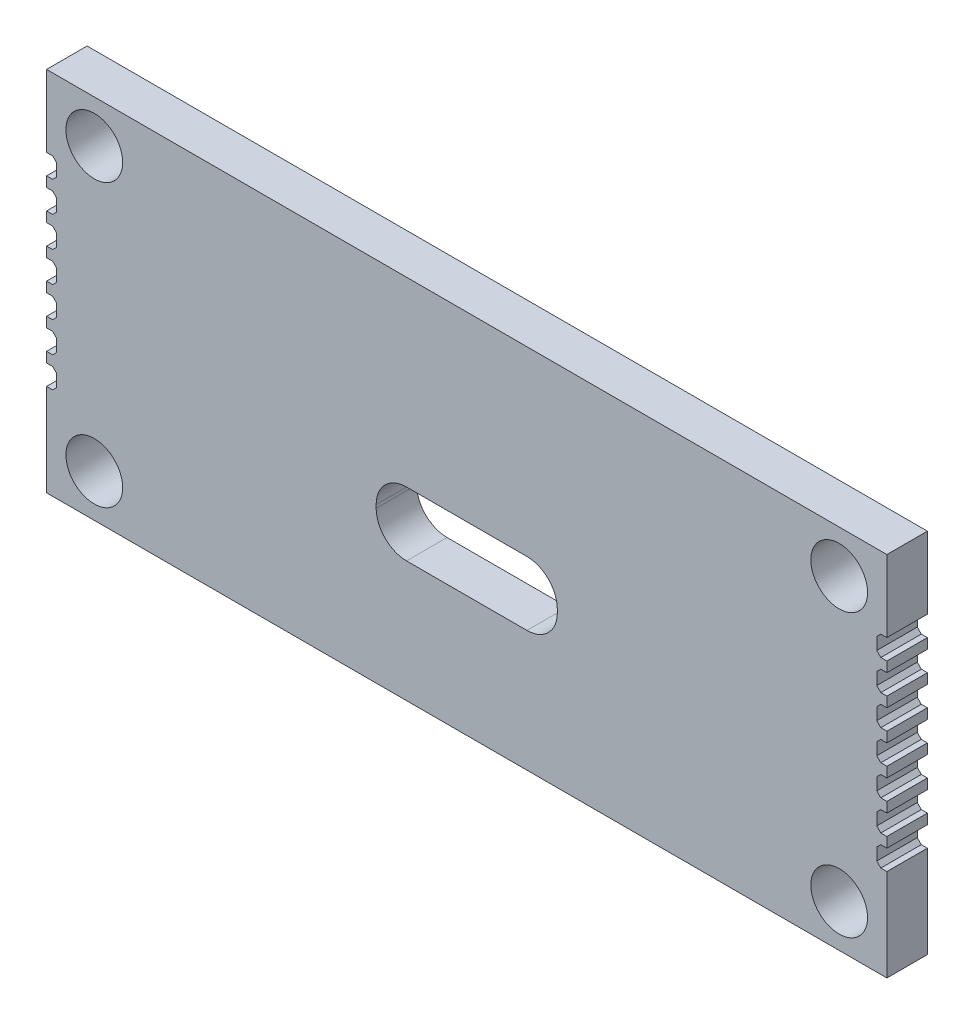
SolidWorks part; units mm, degrees
ref_plane "前视基准面" through (0, 0, 0) normal (0, 0, 1) x (1, 0, 0)
ref_plane "上视基准面" through (0, 0, 0) normal (0, 1, 0) x (1, 0, 0)
ref_plane "右视基准面" through (0, 0, 0) normal (1, 0, 0) x (0, 0, -1)
sketch "草图1" plane through (0, 0, 0) normal (0, 0, 1) x (1, 0, 0)
  line L4 (20.7373, 10.05) -> (20.7373, 13.6)
  line L5 (-20.7373, -4.5) -> (20.7373, -4.5)
  line L6 (-20.7373, 0.05) -> (-20.7373, -4.5)
  line L7 (20.7373, 13.6) -> (-20.7373, 13.6)
  line L8 (20.7373, 10.05) -> (20.7373, 13.6)
  line L9 (-20.7373, -4.5) -> (20.7373, -4.5)
  line L10 (-20.7373, 0.05) -> (-20.7373, -4.5)
  line L11 (20.7373, 13.6) -> (-20.7373, 13.6)
  line L184 (20.4373, 1.55) -> (20.2373, 1.75)
  line L185 (20.4373, 1.55) -> (20.2373, 1.75)
  line L186 (20.7373, 1.55) -> (20.4373, 1.55)
  line L187 (20.7373, 1.55) -> (20.4373, 1.55)
  line L188 (20.7373, 1.05) -> (20.7373, 1.55)
  line L189 (20.7373, 1.05) -> (20.7373, 1.55)
  line L190 (20.4373, 1.05) -> (20.7373, 1.05)
  line L191 (20.4373, 1.05) -> (20.7373, 1.05)
  line L192 (20.2373, 0.85) -> (20.4373, 1.05)
  line L193 (20.2373, 0.85) -> (20.4373, 1.05)
  line L194 (20.2373, 0.25) -> (20.2373, 0.85)
  line L195 (20.2373, 0.25) -> (20.2373, 0.85)
  line L196 (20.4373, 0.05) -> (20.2373, 0.25)
  line L197 (20.4373, 0.05) -> (20.2373, 0.25)
  line L198 (20.7373, 0.05) -> (20.4373, 0.05)
  line L199 (20.7373, 0.05) -> (20.4373, 0.05)
  line L200 (20.7373, -4.5) -> (20.7373, 0.05)
  line L201 (20.7373, -4.5) -> (20.7373, 0.05)
  line L202 (-20.4373, 0.05) -> (-20.7373, 0.05)
  line L203 (-20.4373, 0.05) -> (-20.7373, 0.05)
  line L204 (-20.2373, 0.25) -> (-20.4373, 0.05)
  line L205 (-20.2373, 0.25) -> (-20.4373, 0.05)
  line L206 (-20.2373, 0.85) -> (-20.2373, 0.25)
  line L207 (-20.2373, 0.85) -> (-20.2373, 0.25)
  line L208 (-20.4373, 1.05) -> (-20.2373, 0.85)
  line L209 (-20.4373, 1.05) -> (-20.2373, 0.85)
  line L210 (-20.7373, 1.05) -> (-20.4373, 1.05)
  line L211 (-20.7373, 1.05) -> (-20.4373, 1.05)
  line L212 (-20.7373, 1.55) -> (-20.7373, 1.05)
  line L213 (-20.7373, 1.55) -> (-20.7373, 1.05)
  line L214 (-20.4373, 1.55) -> (-20.7373, 1.55)
  line L215 (-20.4373, 1.55) -> (-20.7373, 1.55)
  line L216 (-20.2373, 1.75) -> (-20.4373, 1.55)
  line L217 (-20.2373, 1.75) -> (-20.4373, 1.55)
  line L218 (-20.2373, 2.35) -> (-20.2373, 1.75)
  line L219 (-20.2373, 2.35) -> (-20.2373, 1.75)
  line L220 (-20.4373, 2.55) -> (-20.2373, 2.35)
  line L221 (-20.4373, 2.55) -> (-20.2373, 2.35)
  line L222 (-20.7373, 2.55) -> (-20.4373, 2.55)
  line L223 (-20.7373, 2.55) -> (-20.4373, 2.55)
  line L224 (-20.7373, 3.05) -> (-20.7373, 2.55)
  line L225 (-20.7373, 3.05) -> (-20.7373, 2.55)
  line L226 (-20.4373, 3.05) -> (-20.7373, 3.05)
  line L227 (-20.4373, 3.05) -> (-20.7373, 3.05)
  line L228 (-20.2373, 3.25) -> (-20.4373, 3.05)
  line L229 (-20.2373, 3.25) -> (-20.4373, 3.05)
  line L230 (-20.2373, 3.85) -> (-20.2373, 3.25)
  line L231 (-20.2373, 3.85) -> (-20.2373, 3.25)
  line L232 (-20.4373, 4.05) -> (-20.2373, 3.85)
  line L233 (-20.4373, 4.05) -> (-20.2373, 3.85)
  line L234 (-20.7373, 4.05) -> (-20.4373, 4.05)
  line L235 (-20.7373, 4.05) -> (-20.4373, 4.05)
  line L236 (-20.7373, 4.55) -> (-20.7373, 4.05)
  line L237 (-20.7373, 4.55) -> (-20.7373, 4.05)
  line L238 (-20.4373, 4.55) -> (-20.7373, 4.55)
  line L239 (-20.4373, 4.55) -> (-20.7373, 4.55)
  line L240 (-20.2373, 4.75) -> (-20.4373, 4.55)
  line L241 (-20.2373, 4.75) -> (-20.4373, 4.55)
  line L242 (-20.2373, 5.35) -> (-20.2373, 4.75)
  line L243 (-20.2373, 5.35) -> (-20.2373, 4.75)
  line L244 (-20.4373, 5.55) -> (-20.2373, 5.35)
  line L245 (-20.4373, 5.55) -> (-20.2373, 5.35)
  line L246 (-20.7373, 5.55) -> (-20.4373, 5.55)
  line L247 (-20.7373, 5.55) -> (-20.4373, 5.55)
  line L248 (-20.7373, 6.05) -> (-20.7373, 5.55)
  line L249 (-20.7373, 6.05) -> (-20.7373, 5.55)
  line L250 (-20.4373, 6.05) -> (-20.7373, 6.05)
  line L251 (-20.4373, 6.05) -> (-20.7373, 6.05)
  line L252 (-20.2373, 6.25) -> (-20.4373, 6.05)
  line L253 (-20.2373, 6.25) -> (-20.4373, 6.05)
  line L254 (-20.2373, 6.85) -> (-20.2373, 6.25)
  line L255 (-20.2373, 6.85) -> (-20.2373, 6.25)
  line L256 (-20.4373, 7.05) -> (-20.2373, 6.85)
  line L257 (-20.4373, 7.05) -> (-20.2373, 6.85)
  line L258 (-20.7373, 7.05) -> (-20.4373, 7.05)
  line L259 (-20.7373, 7.05) -> (-20.4373, 7.05)
  line L260 (-20.7373, 7.55) -> (-20.7373, 7.05)
  line L261 (-20.7373, 7.55) -> (-20.7373, 7.05)
  line L262 (-20.4373, 7.55) -> (-20.7373, 7.55)
  line L263 (-20.4373, 7.55) -> (-20.7373, 7.55)
  line L264 (-20.2373, 7.75) -> (-20.4373, 7.55)
  line L265 (-20.2373, 7.75) -> (-20.4373, 7.55)
  line L266 (-20.2373, 8.35) -> (-20.2373, 7.75)
  line L267 (-20.2373, 8.35) -> (-20.2373, 7.75)
  line L268 (-20.4373, 8.55) -> (-20.2373, 8.35)
  line L269 (-20.4373, 8.55) -> (-20.2373, 8.35)
  line L270 (-20.7373, 8.55) -> (-20.4373, 8.55)
  line L271 (-20.7373, 8.55) -> (-20.4373, 8.55)
  line L272 (-20.7373, 9.05) -> (-20.7373, 8.55)
  line L273 (-20.7373, 9.05) -> (-20.7373, 8.55)
  line L274 (-20.4373, 9.05) -> (-20.7373, 9.05)
  line L275 (-20.4373, 9.05) -> (-20.7373, 9.05)
  line L276 (-20.2373, 9.25) -> (-20.4373, 9.05)
  line L277 (-20.2373, 9.25) -> (-20.4373, 9.05)
  line L278 (-20.2373, 9.85) -> (-20.2373, 9.25)
  line L279 (-20.2373, 9.85) -> (-20.2373, 9.25)
  line L280 (-20.4373, 10.05) -> (-20.2373, 9.85)
  line L281 (-20.4373, 10.05) -> (-20.2373, 9.85)
  line L282 (-20.7373, 10.05) -> (-20.4373, 10.05)
  line L283 (-20.7373, 10.05) -> (-20.4373, 10.05)
  line L284 (-20.7373, 13.6) -> (-20.7373, 10.05)
  line L285 (-20.7373, 13.6) -> (-20.7373, 10.05)
  line L286 (20.4373, 10.05) -> (20.7373, 10.05)
  line L287 (20.4373, 10.05) -> (20.7373, 10.05)
  line L288 (20.2373, 9.85) -> (20.4373, 10.05)
  line L289 (20.2373, 9.85) -> (20.4373, 10.05)
  line L290 (20.2373, 9.25) -> (20.2373, 9.85)
  line L291 (20.2373, 9.25) -> (20.2373, 9.85)
  line L292 (20.4373, 9.05) -> (20.2373, 9.25)
  line L293 (20.4373, 9.05) -> (20.2373, 9.25)
  line L294 (20.7373, 9.05) -> (20.4373, 9.05)
  line L295 (20.7373, 9.05) -> (20.4373, 9.05)
  line L296 (20.7373, 8.55) -> (20.7373, 9.05)
  line L297 (20.7373, 8.55) -> (20.7373, 9.05)
  line L298 (20.4373, 8.55) -> (20.7373, 8.55)
  line L299 (20.4373, 8.55) -> (20.7373, 8.55)
  line L300 (20.2373, 8.35) -> (20.4373, 8.55)
  line L301 (20.2373, 8.35) -> (20.4373, 8.55)
  line L302 (20.2373, 7.75) -> (20.2373, 8.35)
  line L303 (20.2373, 7.75) -> (20.2373, 8.35)
  line L304 (20.4373, 7.55) -> (20.2373, 7.75)
  line L305 (20.4373, 7.55) -> (20.2373, 7.75)
  line L306 (20.7373, 7.55) -> (20.4373, 7.55)
  line L307 (20.7373, 7.55) -> (20.4373, 7.55)
  line L308 (20.7373, 7.05) -> (20.7373, 7.55)
  line L309 (20.7373, 7.05) -> (20.7373, 7.55)
  line L310 (20.4373, 7.05) -> (20.7373, 7.05)
  line L311 (20.4373, 7.05) -> (20.7373, 7.05)
  line L312 (20.2373, 6.85) -> (20.4373, 7.05)
  line L313 (20.2373, 6.85) -> (20.4373, 7.05)
  line L314 (20.2373, 6.25) -> (20.2373, 6.85)
  line L315 (20.2373, 6.25) -> (20.2373, 6.85)
  line L316 (20.4373, 6.05) -> (20.2373, 6.25)
  line L317 (20.4373, 6.05) -> (20.2373, 6.25)
  line L318 (20.7373, 6.05) -> (20.4373, 6.05)
  line L319 (20.7373, 6.05) -> (20.4373, 6.05)
  line L320 (20.7373, 5.55) -> (20.7373, 6.05)
  line L321 (20.7373, 5.55) -> (20.7373, 6.05)
  line L322 (20.4373, 5.55) -> (20.7373, 5.55)
  line L323 (20.4373, 5.55) -> (20.7373, 5.55)
  line L324 (20.2373, 5.35) -> (20.4373, 5.55)
  line L325 (20.2373, 5.35) -> (20.4373, 5.55)
  line L326 (20.2373, 4.75) -> (20.2373, 5.35)
  line L327 (20.2373, 4.75) -> (20.2373, 5.35)
  line L328 (20.4373, 4.55) -> (20.2373, 4.75)
  line L329 (20.4373, 4.55) -> (20.2373, 4.75)
  line L330 (20.7373, 4.55) -> (20.4373, 4.55)
  line L331 (20.7373, 4.55) -> (20.4373, 4.55)
  line L332 (20.7373, 4.05) -> (20.7373, 4.55)
  line L333 (20.7373, 4.05) -> (20.7373, 4.55)
  line L334 (20.4373, 4.05) -> (20.7373, 4.05)
  line L335 (20.4373, 4.05) -> (20.7373, 4.05)
  line L336 (20.2373, 3.85) -> (20.4373, 4.05)
  line L337 (20.2373, 3.85) -> (20.4373, 4.05)
  line L338 (20.2373, 3.25) -> (20.2373, 3.85)
  line L339 (20.2373, 3.25) -> (20.2373, 3.85)
  line L340 (20.4373, 3.05) -> (20.2373, 3.25)
  line L341 (20.4373, 3.05) -> (20.2373, 3.25)
  line L342 (20.7373, 3.05) -> (20.4373, 3.05)
  line L343 (20.7373, 3.05) -> (20.4373, 3.05)
  line L344 (20.7373, 2.55) -> (20.7373, 3.05)
  line L345 (20.7373, 2.55) -> (20.7373, 3.05)
  line L346 (20.4373, 2.55) -> (20.7373, 2.55)
  line L347 (20.4373, 2.55) -> (20.7373, 2.55)
  line L348 (20.2373, 2.35) -> (20.4373, 2.55)
  line L349 (20.2373, 2.35) -> (20.4373, 2.55)
  line L350 (20.2373, 1.75) -> (20.2373, 2.35)
  line L351 (20.2373, 1.75) -> (20.2373, 2.35)
  circle A0 centre (-18.3831, 11.5) radius 1.4 construction
  circle A1 centre (-18.3831, -2.4) radius 1.4 construction
  circle A2 centre (18.3831, -2.4) radius 1.4 construction
  circle A3 centre (18.3831, 11.5) radius 1.4 construction
  circle A4 centre (-18.3831, 11.5) radius 1.4
  circle A5 centre (-18.3831, -2.4) radius 1.4
  circle A6 centre (18.3831, -2.4) radius 1.4
  circle A7 centre (18.3831, 11.5) radius 1.4
  dimension "D1" = 0
extrude "凸台-拉伸2" add sketch "草图1" along normal blind 2 contours A4 | A5 | A7 | A6 | L8 L11 L285 L283 L281 L279 L277 L275 L273 L271 L269 L267 L265 L263 L261 L259 L257 L255 L253 L251 L249 L247 L245 L243 L241 L239 L237 L235 L233 L231 L229 L227 L225 L223 L221 L219 L217 L215 L213 L211 L209 L207 L205 L203 L10 L9 L201 L199 L197 L195 L193 L191 L189 L187 L185 L351 L349 L347 L345 L343 L341 L339 L337 L335 L333 L331 L329 L327 L325 L323 L321 L319 L317 L315 L313 L311 L309 L307 L305 L303 L301 L299 L297 L295 L293 L291 L289 L287
sketch "草图2" plane through (0, 0, 0) normal (0, 0, -1) x (-1, 0, 0)
  line L0 (2.97, 4.6339) -> (-2.97, 4.6339) construction
  line L1 (2.97, 4.6339) -> (-2.97, 4.6339)
  line L2 (-4.47, 3.1339) -> (-4.47, 2.9739) construction
  line L3 (-4.47, 3.1339) -> (-4.47, 2.9739)
  line L4 (4.47, 2.9739) -> (4.47, 3.1339) construction
  line L5 (4.47, 2.9739) -> (4.47, 3.1339)
  line L6 (-0.05, 1.4739) -> (-2.97, 1.4739) construction
  line L7 (-0.05, 1.4739) -> (-2.97, 1.4739)
  line L9 (-0.05, 1.4739) -> (2.97, 1.4739)
  arc A0 (-2.97, 4.6339) -> (-4.47, 3.1339) centre (-2.97, 3.1339) ccw construction
  arc A1 (-2.97, 4.6339) -> (-4.47, 3.1339) centre (-2.97, 3.1339) ccw
  arc A2 (4.47, 3.1339) -> (2.97, 4.6339) centre (2.97, 3.1339) ccw construction
  arc A3 (4.47, 3.1339) -> (2.97, 4.6339) centre (2.97, 3.1339) ccw
  arc A4 (-4.47, 2.9739) -> (-2.97, 1.4739) centre (-2.97, 2.9739) ccw construction
  arc A5 (-4.47, 2.9739) -> (-2.97, 1.4739) centre (-2.97, 2.9739) ccw
  arc A6 (2.97, 1.4739) -> (4.47, 2.9739) centre (2.97, 2.9739) ccw construction
  arc A7 (2.97, 1.4739) -> (4.47, 2.9739) centre (2.97, 2.9739) ccw
extrude "切除-拉伸1" cut sketch "草图2" against normal up to next
